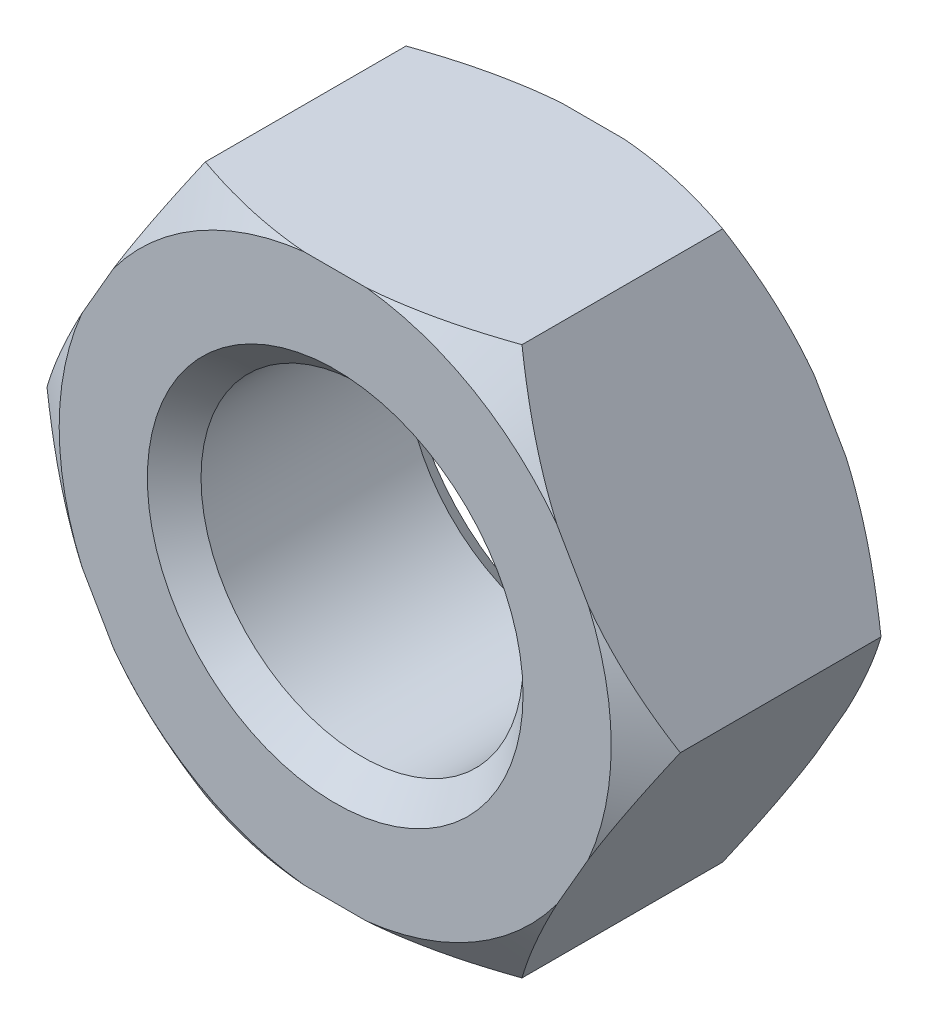
SolidWorks part; units mm, degrees
material "Plain Carbon Steel"
ref_plane "Спереди" through (0, 0, 0) normal (0, 0, 1) x (1, 0, 0)
ref_plane "Сверху" through (0, 0, 0) normal (0, 1, 0) x (1, 0, 0)
ref_plane "Справа" through (0, 0, 0) normal (1, 0, 0) x (0, 0, -1)
sketch "Sketch1" plane through (0, 0, 0) normal (0, 0, 1) x (1, 0, 0)
  line L1 (2.95, 0) -> (1.475, 2.5548)
  line L2 (1.475, 2.5548) -> (-1.475, 2.5548)
  line L3 (-1.475, 2.5548) -> (-2.95, 0)
  line L4 (-2.95, 0) -> (-1.475, -2.5548)
  line L5 (-1.475, -2.5548) -> (1.475, -2.5548)
  line L6 (1.475, -2.5548) -> (2.95, 0)
  circle A0 centre (0, 0) radius 2.5548 construction
  circle A1 centre (0, 0) radius 1.5
  dimension "D1" = 3
  dimension "D2" = 5.9
extrude "Boss-Extrude1" add sketch "Sketch1" along normal blind 2.4
chamfer "Chamfer1" distance 0.25 angle 45 2 edges at (1.5, 0, 0) (1.5, 0, 2.4)
sketch "Sketch2" plane through (0, 0, 0) normal (0, 1, 0) x (1, 0, 0)
  line L0 (0, -2.45) -> (0, 0.05) construction
  line L1 (-1, -2.45) -> (-2.5, -2.45)
  line L2 (-2.5, -2.45) -> (-3.1328, -2.0069)
  line L3 (-3.1328, -2.0069) -> (-3.1328, -0.3931)
  line L4 (-3.1328, -0.3931) -> (-2.5, 0.05)
  line L5 (-2.5, 0.05) -> (-1, 0.05)
  line L6 (-1, 0.05) -> (-1, 1.9813)
  line L7 (-1, 1.9813) -> (-7.7509, 1.9813)
  line L8 (-7.7509, 1.9813) -> (-7.7509, -6.9829)
  line L9 (-7.7509, -6.9829) -> (-1, -6.9829)
  line L10 (-1, -6.9829) -> (-1, -2.45)
  line L11 (-2.95, -2.4) -> (-1.475, -2.4) construction
  line L14 (-2.95, 0) -> (-1.475, 0) construction
  dimension "D1" = 1
  dimension "D2" = 35
  dimension "D3" = 35
  dimension "D4" = 1.5
  dimension "D5" = 0.05
  dimension "D6" = 0.05
revolve "Cut-Revolve1" cut sketch "Sketch2" angle 360 about L0
